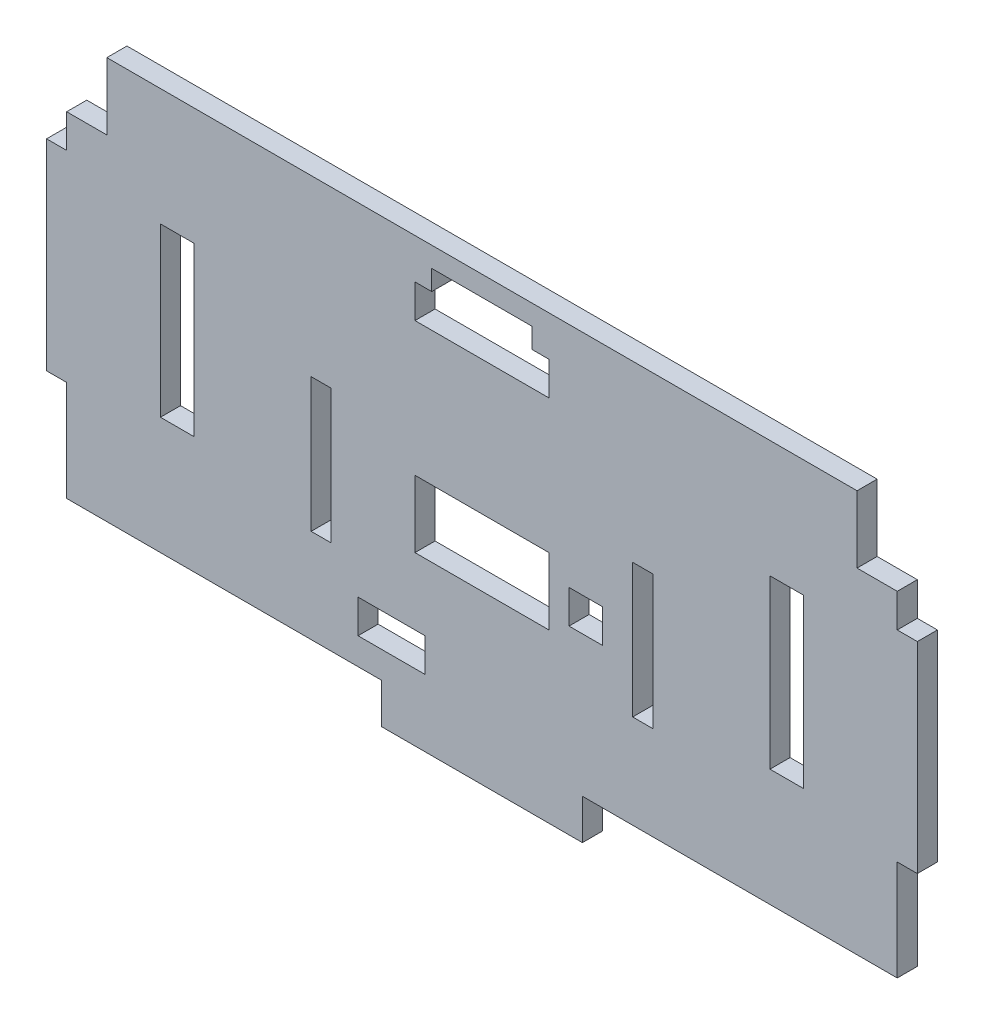
SolidWorks part; units mm, degrees
ref_plane "Front Plane" through (0, 0, 0) normal (0, 0, 1) x (1, 0, 0)
ref_plane "Top Plane" through (0, 0, 0) normal (0, 1, 0) x (1, 0, 0)
ref_plane "Right Plane" through (0, 0, 0) normal (1, 0, 0) x (0, 0, -1)
sketch "Sketch1" plane through (0, 0, 0) normal (0, 0, 1) x (1, 0, 0)
  line L0 (0, 0) -> (47, 0)
  line L1 (47, 0) -> (47, -6)
  line L2 (47, -6) -> (77, -6)
  line L3 (77, -6) -> (77, 0)
  line L4 (77, 0) -> (124, 0)
  line L5 (124, 0) -> (124, 15)
  line L6 (124, 15) -> (127, 15)
  line L7 (127, 15) -> (127, 45)
  line L8 (127, 45) -> (124, 45)
  line L9 (124, 45) -> (124, 60)
  line L10 (124, 60) -> (0, 60)
  line L11 (0, 60) -> (0, 45)
  line L12 (0, 45) -> (-3, 45)
  line L13 (-3, 45) -> (-3, 15)
  line L14 (-3, 15) -> (0, 15)
  line L15 (0, 15) -> (0, 0)
  dimension "D1" = 124
  dimension "D2" = 60
  dimension "D3" = 3
  dimension "D4" = 30
  dimension "D5" = 30
  dimension "D6" = 6
extrude "Boss-Extrude1" add sketch "Sketch1" along normal blind 3
sketch "Sketch2" plane through (0, 0, 3) normal (0, 0, 1) x (1, 0, 0)
  line L0 (124, 60) -> (0, 60) construction
  line L1 (0, 60) -> (6, 60)
  line L2 (0, 60) -> (0, 50)
  line L3 (0, 50) -> (6, 50)
  line L4 (6, 60) -> (6, 50)
  line L6 (118, 60) -> (124, 60)
  line L7 (118, 60) -> (118, 50)
  line L8 (118, 50) -> (124, 50)
  line L9 (124, 60) -> (124, 50)
  line L13 (0, 60) -> (0, 45) construction
  line L14 (124, 45) -> (124, 60) construction
  dimension "D1" = 6
  dimension "D2" = 10
extrude "Cut-Extrude1" cut sketch "Sketch2" against normal through all
sketch "Sketch3" plane through (0, 0, 3) normal (0, 0, 1) x (1, 0, 0)
  line L1 (54.5, 57) -> (69.5, 57)
  line L2 (54.5, 57) -> (54.5, 54)
  line L3 (52, 54) -> (54.5, 54)
  line L4 (69.5, 57) -> (69.5, 54)
  line L5 (36.5, 34) -> (39.5, 34)
  line L6 (36.5, 34) -> (36.5, 14)
  line L7 (36.5, 14) -> (39.5, 14)
  line L8 (39.5, 34) -> (39.5, 14)
  line L9 (84.5, 34) -> (87.5, 34)
  line L10 (84.5, 34) -> (84.5, 14)
  line L11 (84.5, 14) -> (87.5, 14)
  line L12 (87.5, 34) -> (87.5, 14)
  line L13 (124, 0) -> (124, 15) construction
  line L14 (72, 54) -> (69.5, 54)
  line L15 (118, 60) -> (6, 60) construction
  line L16 (52, 54) -> (52, 49)
  line L17 (52, 49) -> (72, 49)
  line L18 (72, 54) -> (72, 49)
  line L19 (52, 29) -> (72, 29)
  line L20 (52, 29) -> (52, 19)
  line L21 (52, 19) -> (72, 19)
  line L22 (72, 29) -> (72, 19)
  line L23 (43.5, 9) -> (53.5, 9)
  line L24 (43.5, 9) -> (43.5, 4)
  line L25 (43.5, 4) -> (53.5, 4)
  line L26 (53.5, 9) -> (53.5, 4)
  line L27 (75, 26) -> (80, 26)
  line L28 (75, 26) -> (75, 21)
  line L29 (75, 21) -> (80, 21)
  line L30 (80, 26) -> (80, 21)
  line L31 (47, -6) -> (77, -6) construction
  dimension "D1" = 45
  dimension "D2" = 3
  dimension "D3" = 20
  dimension "D4" = 3
  dimension "D5" = 15
  dimension "D6" = 36.5
  dimension "D7" = 15
  dimension "D8" = 10
  dimension "D9" = 20
  dimension "D10" = 5
  dimension "D11" = 25
  dimension "D12" = 20
  dimension "D13" = 5
  dimension "D14" = 5
  dimension "D15" = 3
  dimension "D16" = 7
  dimension "D17" = 10
  dimension "D18" = 5
  dimension "D19" = 10
  dimension "D20" = 4
extrude "Cut-Extrude2" cut sketch "Sketch3" against normal through all
sketch "Sketch4" plane through (0, 0, 3) normal (0, 0, 1) x (1, 0, 0)
  line L0 (118, 60) -> (6, 60) construction
  line L1 (124, 0) -> (124, 15) construction
  line L9 (14, 42.5) -> (19, 42.5)
  line L10 (14, 42.5) -> (14, 17.5)
  line L11 (14, 17.5) -> (19, 17.5)
  line L12 (19, 42.5) -> (19, 17.5)
  line L13 (105, 42.5) -> (110, 42.5)
  line L14 (105, 42.5) -> (105, 17.5)
  line L15 (105, 17.5) -> (110, 17.5)
  line L16 (110, 42.5) -> (110, 17.5)
  line L17 (0, 15) -> (0, 0) construction
  dimension "D1" = 14
  dimension "D4" = 5
  dimension "D5" = 25
  dimension "D6" = 17.5
  dimension "D7" = 14
extrude "Cut-Extrude3" cut sketch "Sketch4" against normal through all
